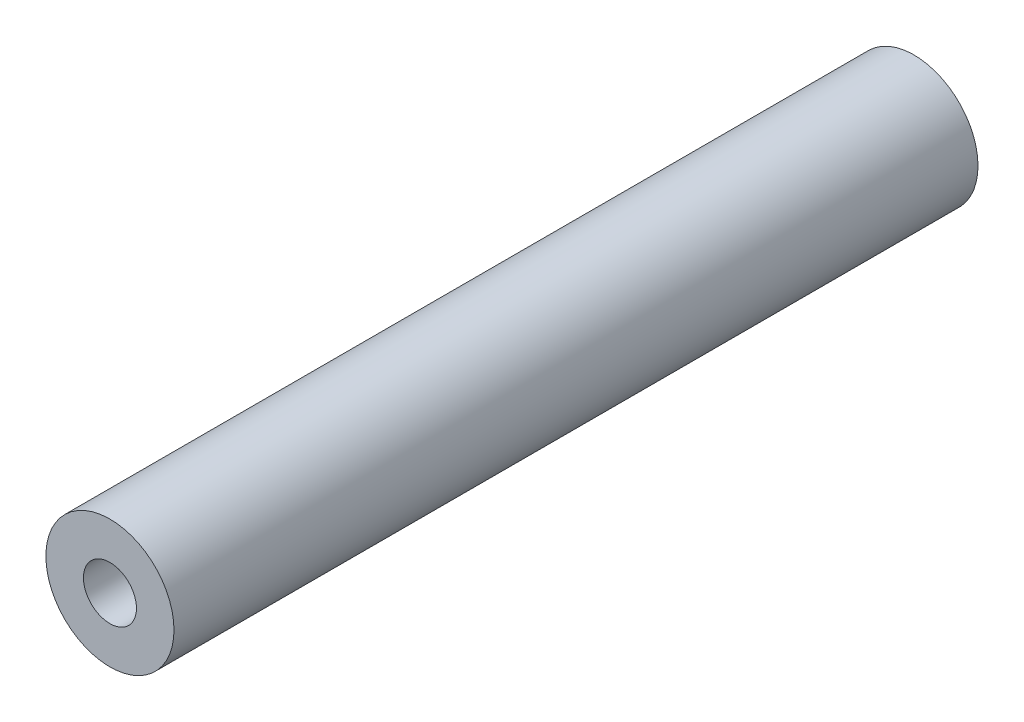
SolidWorks part; units mm, degrees
ref_plane "Front Plane" through (0, 0, 0) normal (0, 0, 1) x (1, 0, 0)
ref_plane "Top Plane" through (0, 0, 0) normal (0, 1, 0) x (1, 0, 0)
ref_plane "Right Plane" through (0, 0, 0) normal (1, 0, 0) x (0, 0, -1)
sketch "Sketch2" plane through (0, 0, 0) normal (0, 0, 1) x (1, 0, 0)
  circle A0 centre (0, 0) radius 7.366
  circle A1 centre (0, 0) radius 3.048
  dimension "D1" = 14.732
  dimension "D2" = 6.096
extrude "Boss-Extrude1" add sketch "Sketch2" along normal blind 92.456
